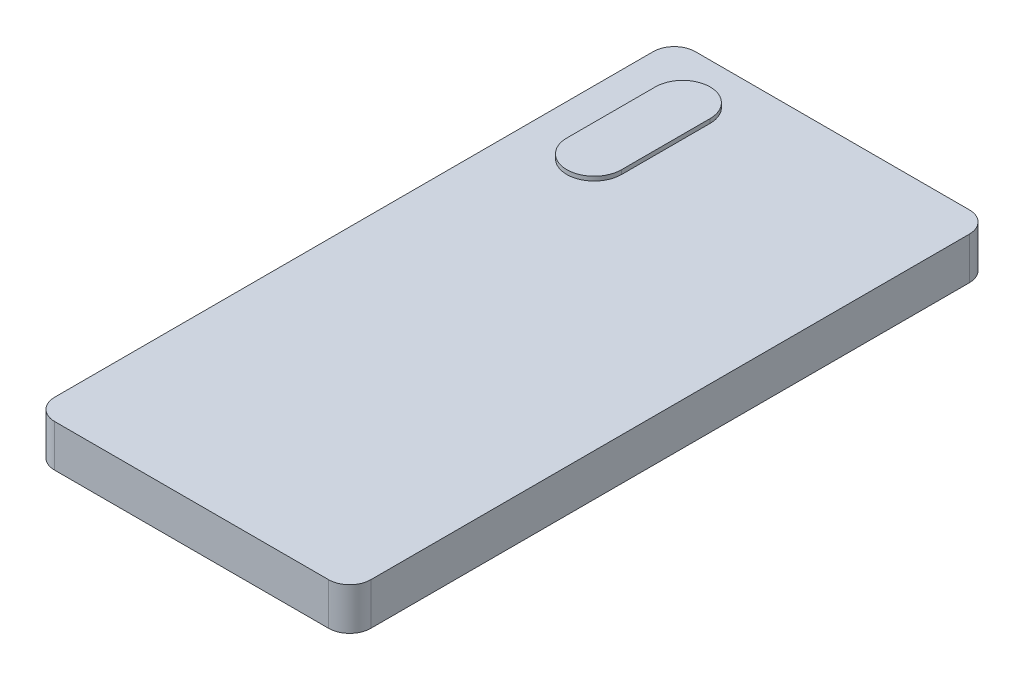
SolidWorks part; units mm, degrees
ref_plane "前视基准面" through (0, 0, 0) normal (0, 0, 1) x (1, 0, 0)
ref_plane "上视基准面" through (0, 0, 0) normal (0, 1, 0) x (1, 0, 0)
ref_plane "右视基准面" through (0, 0, 0) normal (1, 0, 0) x (0, 0, -1)
other "Configuration Table"
sketch "草图1" plane through (0, 0, 0) normal (0, 1, 0) x (1, 0, 0)
  line L1 (-32.5, 76) -> (32.5, 76)
  line L2 (-37.5, 71) -> (-37.5, -71)
  line L3 (-32.5, -76) -> (32.5, -76)
  line L4 (37.5, 71) -> (37.5, -71)
  line L5 (-37.5, 76) -> (37.5, -76) construction
  line L6 (-37.5, -76) -> (37.5, 76) construction
  arc A0 (-37.5, -71) -> (-32.5, -76) centre (-32.5, -71) ccw
  arc A1 (37.5, -71) -> (32.5, -76) centre (32.5, -71) cw
  arc A2 (37.5, 71) -> (32.5, 76) centre (32.5, 71) ccw
  arc A3 (-37.5, 71) -> (-32.5, 76) centre (-32.5, 71) cw
  point P0 (0, 0)
  dimension "D3" = 5
  dimension "D1" = 75
  dimension "D2" = 152
extrude "凸台-拉伸1" add sketch "草图1" along normal blind 10
sketch "草图2" plane through (0, 10, 0) normal (0, 1, 0) x (1, 0, 0)
  line L0 (-22.5, 54.4733) -> (-22.5, -49945.5267) construction
  line L1 (-37.5, 71) -> (-37.5, -71) construction
  line L2 (32.5, 76) -> (-32.5, 76) construction
  line L3 (-29, 63) -> (-29, 42)
  line L4 (-16, 63) -> (-16, 42)
  arc A0 (-29, 63) -> (-16, 63) centre (-22.5, 63) cw
  arc A1 (-29, 42) -> (-16, 42) centre (-22.5, 42) ccw
  point P4 (-174.0632, 74.7739)
  point P5 (-22.5, 63)
  point P6 (-22.5, 42)
  dimension "D4" = 6.5
  dimension "D5" = 6.5
  dimension "D1" = 15
  dimension "D2" = 21
  dimension "D3" = 13
extrude "凸台-拉伸2" add sketch "草图2" along normal blind 1
